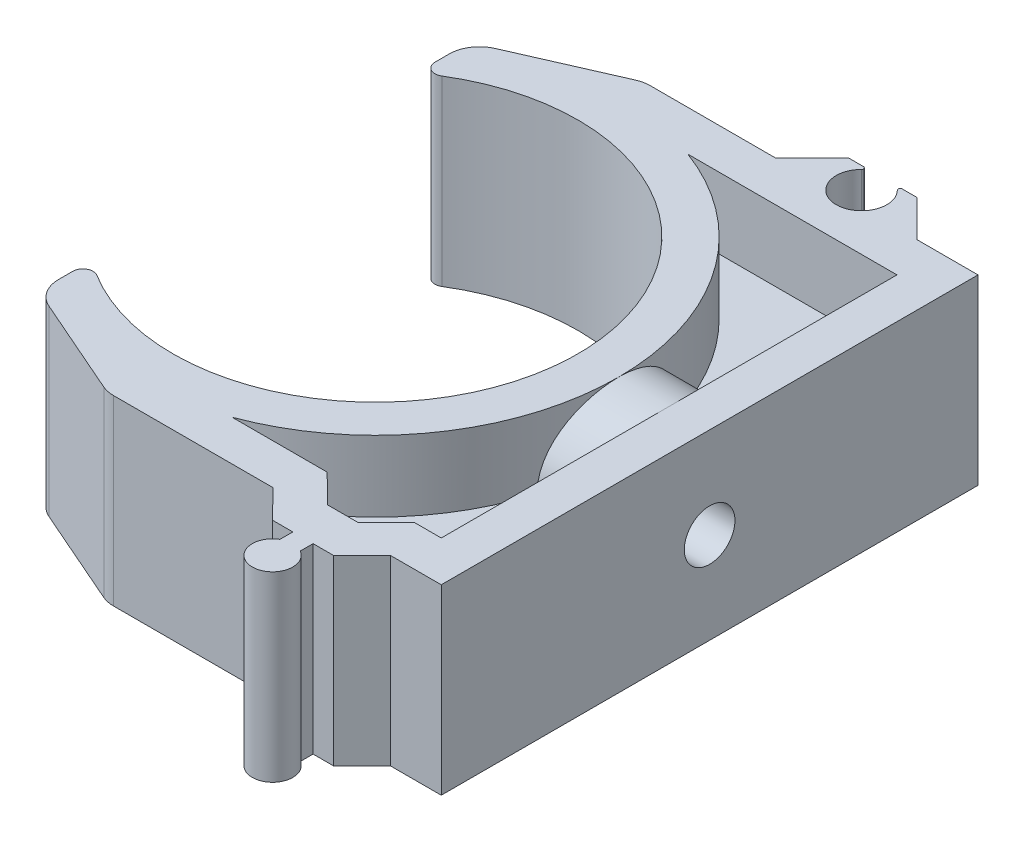
SolidWorks part; units mm, degrees
ref_plane "Front Plane" through (0, 0, 0) normal (0, 0, 1) x (1, 0, 0)
ref_plane "Top Plane" through (0, 0, 0) normal (0, 1, 0) x (1, 0, 0)
ref_plane "Right Plane" through (0, 0, 0) normal (1, 0, 0) x (0, 0, -1)
sketch "Sketch1" plane through (0, 0, 0) normal (0, 1, 0) x (1, 0, 0)
  line L0 (-22.5, -17.8885) -> (-22.5, -19.288)
  line L1 (-9.8708, 26.5) -> (2.5, 26.5)
  line L2 (-22.5, 19.2753) -> (-22.5, 17.8885)
  line L3 (-9.8725, -26.5) -> (5.88, -26.5)
  line L4 (22.5, 26.5) -> (22.5, -26.5)
  line L5 (-22.5, 26.5) -> (22.5, -26.5) construction
  line L6 (-22.5, -26.5) -> (22.5, 26.5) construction
  line L7 (22.5, 26.5) -> (16.5, 26.5)
  line L8 (-11.0749, -26.2485) -> (-20.7025, -22.0364)
  line L9 (-11.0762, 26.2472) -> (-20.7025, 22.0238)
  line L10 (-20.7025, 22.0238) -> (-20.7053, 22.0225)
  line L13 (16.5, 26.5) -> (22.5, 26.5)
  line L15 (7.5893, 30.1077) -> (6.1555, 30.1077)
  line L16 (6.1555, 30.1077) -> (2.5, 26.5)
  line L17 (11.4107, 30.1077) -> (12.8445, 30.1077)
  line L18 (12.8445, 30.1077) -> (16.5, 26.5)
  line L19 (22.5, -26.5) -> (17.5, -26.5)
  line L20 (17.5, -26.5) -> (14.653, -29.3097)
  line L21 (14.653, -29.3097) -> (12.653, -29.3097)
  line L22 (8.653, -29.3097) -> (5.88, -26.5)
  line L23 (10.653, -29.3097) -> (8.653, -29.3097)
  line L24 (17.5, -26.5) -> (22.5, -26.5)
  line L25 (10.653, -29.3097) -> (10.653, -30.5777)
  line L26 (12.653, -29.3097) -> (12.653, -30.5777)
  arc A0 (-20.9762, -17.0367) -> (-20.9762, 17.0367) centre (-10.5, 0) ccw
  arc A1 (-9.8725, -26.5) -> (-11.0749, -26.2485) centre (-9.8725, -23.5) cw
  arc A2 (-20.7025, -22.0364) -> (-22.5, -19.288) centre (-19.5, -19.288) cw
  arc A3 (-20.9762, -17.0367) -> (-22.5, -17.8885) centre (-21.5, -17.8885) ccw
  arc A4 (-20.9762, 17.0367) -> (-22.5, 17.8885) centre (-21.5, 17.8885) cw
  arc A5 (-20.7053, 22.0225) -> (-22.5, 19.2753) centre (-19.5, 19.2753) ccw
  arc A6 (-9.8708, 26.5) -> (-11.0762, 26.2472) centre (-9.8708, 23.5) ccw
  arc A7 (7.7308, 29.7664) -> (11.2692, 29.7664) centre (9.5, 28) ccw
  arc A8 (11.4107, 30.1077) -> (11.2692, 29.7664) centre (11.4107, 29.9077) ccw
  arc A9 (7.5893, 30.1077) -> (7.7308, 29.7664) centre (7.5893, 29.9077) cw
  arc A10 (10.653, -30.5777) -> (12.653, -30.5777) centre (11.653, -32.3097) ccw
  point P0 (0, 0)
  point P17 (-22.5, -16)
  point P36 (10.8445, 30.1077)
  point P39 (8.1555, 30.1077)
  dimension "D3" = 40
  dimension "D4" = 33
  dimension "D5" = 3
  dimension "D6" = 1
  dimension "D7" = 1
  dimension "D8" = 3
  dimension "D9" = 3
  dimension "D10" = 5
  dimension "D16" = 0.2
  dimension "D20" = 4
  dimension "D1" = 53
  dimension "D2" = 45
  dimension "D11" = 13
  dimension "D12" = 1.5
  dimension "D13" = 6
  dimension "D14" = 2
  dimension "D15" = 2
  dimension "D17" = 5
  dimension "D18" = 4
  dimension "D19" = 6
extrude "Boss-Extrude1" add sketch "Sketch1" along normal blind 18 contours L25 A10 L26 L21 L20 L19 L4 L7 L18 L17 A8 A7 A9 L15 L16 L1 A6 L9 L10 A5 L2 A4 A0 A3 L0 A2 L8 A1 L3 L22 L23
sketch "Sketch2" plane through (0, 0, 0) normal (0, -1, 0) x (1, 0, 0)
  line L0 (18.5, 22.5) -> (18.5, -22.5)
  line L1 (18.5, -22.5) -> (-2.1484, -22.5)
  line L2 (18.5, 22.5) -> (15.8433, 22.5)
  line L3 (22.5, 26.5) -> (17.5, 26.5) construction
  line L4 (22.5, -26.5) -> (22.5, 26.5) construction
  line L5 (22.5, -26.5) -> (16.5, -26.5) construction
  line L6 (7.2386, 22.5) -> (-2.1484, 22.5)
  line L9 (15.8433, 22.5) -> (13.0393, 25.2822)
  line L10 (13.0393, 25.2822) -> (10.0393, 25.282)
  line L11 (10.0393, 25.282) -> (7.2386, 22.5)
  arc A0 (-2.1484, -22.5) -> (-2.1484, 22.5) centre (-10.5, 0) ccw
  dimension "D1" = 48
  dimension "D2" = 4
  dimension "D3" = 4
  dimension "D4" = 4
  dimension "D5" = 3
  dimension "D6" = 3.9477
  dimension "D7" = 3.95
  dimension "D8" = 2.6567
extrude "Cut-Extrude1" cut sketch "Sketch2" against normal blind 7
ref_plane "Plane1" through (0, 9, 0) normal (0, -1, 0) x (-1, 0, 0)
mirror "Mirror1" about plane through (0, 9, 0) normal (0, -1, 0) of "Cut-Extrude1"
sketch "Sketch3" plane through (18.5, 0, 0) normal (-1, 0, 0) x (0, 0, 1)
  line L0 (-22.5, 7) -> (22.5, 7) construction
  line L1 (7, 7) -> (-7, 7)
  arc A0 (-7, 7) -> (7, 7) centre (0, 7) ccw
extrude "Boss-Extrude2" add sketch "Sketch3" along normal blind 7
mirror "Mirror2" about plane through (0, 9, 0) normal (0, -1, 0) of "Boss-Extrude2"
sketch "Sketch4" plane through (22.5, 0, 0) normal (1, 0, 0) x (0, 0, -1)
  circle A0 centre (0, 9) radius 2.5
  dimension "D1" = 5
extrude "Cut-Extrude2" cut sketch "Sketch4" against normal blind 6
ref_plane "Plane2" through (9.5, 0, 0) normal (1, 0, 0) x (0, 0, -1)
sketch "Sketch5" plane through (9.5, 0, 0) normal (1, 0, 0) x (0, 0, -1)
  line L7 (-24.75, 9) -> (24.75, 9) construction
  circle A0 centre (0, 9) radius 5.75
  point P0 (0, 9)
  dimension "D1" = 11.5
extrude "Cut-Extrude3" cut sketch "Sketch5" against normal blind 7
sketch "Sketch6" plane through (9.5, 0, 0) normal (-1, 0, 0) x (0, 0, 1)
  circle A0 centre (0, 9) radius 5.75
extrude "Cut-Extrude4" cut sketch "Sketch6" against normal blind 7
